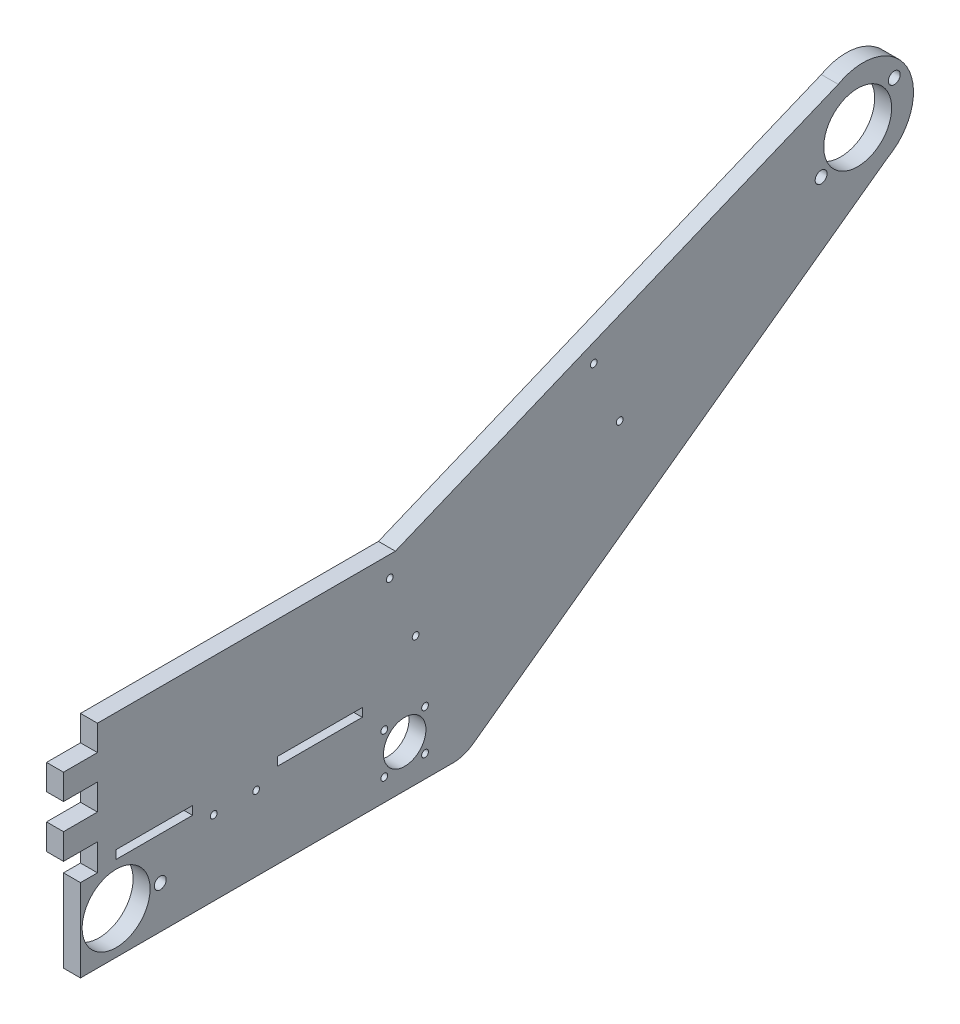
SolidWorks part; units mm, degrees
ref_plane "정면" through (0, 0, 0) normal (0, 0, 1) x (1, 0, 0)
ref_plane "윗면" through (0, 0, 0) normal (0, 1, 0) x (1, 0, 0)
ref_plane "우측면" through (0, 0, 0) normal (1, 0, 0) x (0, 0, -1)
sketch "스케치1" plane through (0, 0, 0) normal (1, 0, 0) x (0, 0, -1)
  line L0 (-325, 0) -> (325, 0) construction
  line L1 (325, 0) -> (591.861, 180) construction
  line L6 (-339, -14) -> (-311, -14) construction
  line L15 (-339, 14) -> (-311, 14) construction
  line L16 (-339, 14) -> (-339, -14) construction
  line L18 (-311, 14) -> (-311, -14) construction
  line L19 (-350, -25) -> (353.4809, -25)
  line L20 (311, 14) -> (311, -14) construction
  line L21 (339, 14) -> (339, -14) construction
  line L22 (339, 14) -> (311, 14) construction
  line L23 (339, -14) -> (311, -14) construction
  line L24 (-350, -25) -> (-350, 30)
  line L25 (300, 25) -> (350, 25) construction
  line L26 (-300, 25) -> (-350, 25) construction
  line L27 (-300, 25) -> (-300, -25) construction
  line L28 (300, 25) -> (300, -25) construction
  line L31 (365.2669, -21.1583) -> (609.4584, 155.7033)
  line L32 (580.4109, 207.729) -> (150, 30)
  line L34 (350, 25) -> (350, -25) construction
  line L35 (46, 52.6531) -> (46, -51.2062) construction
  line L36 (150, 37.2232) -> (150, -42.9076) construction
  line L39 (-350, 30) -> (150, 30)
  circle A0 centre (-325, 0) radius 12.5 construction
  circle A2 centre (-337, -12) radius 2 construction
  circle A3 centre (-313, -12) radius 2 construction
  circle A4 centre (-313, 12) radius 2 construction
  circle A5 centre (-337, 12) radius 2 construction
  circle A6 centre (337, 12) radius 2 construction
  circle A7 centre (313, 12) radius 2 construction
  circle A8 centre (313, -12) radius 2 construction
  circle A9 centre (337, -12) radius 2 construction
  circle A10 centre (325, 0) radius 12.5 construction
  circle A11 centre (0, 0) radius 7.5 construction
  circle A12 centre (0, 0) radius 20 construction
  circle A13 centre (-26, 0) radius 3.5 construction
  circle A14 centre (26, 0) radius 3.5 construction
  circle A15 centre (591.861, 180) radius 7.5 construction
  circle A16 centre (570.306, 165.461) radius 3.5 construction
  circle A17 centre (613.416, 194.539) radius 3.5 construction
  circle A18 centre (591.861, 180) radius 20 construction
  arc A24 (365.2669, -21.1583) -> (353.4809, -25) centre (353.4809, -5) cw
  arc A26 (580.4109, 207.729) -> (609.4584, 155.7033) centre (594.9347, 181.7161) cw
  point P3 (0, 0)
  dimension "D6" = 20
  dimension "D5" = 50
  dimension "D1" = 55
  dimension "D2" = 146
  dimension "D3" = 650
  dimension "D4" = 180
  dimension "D7" = 26
  dimension "D8" = 944.9347
extrude "보스-돌출2" add sketch "스케치1" along normal blind 10
sketch "스케치3" plane through (10, 0, 0) normal (1, 0, 0) x (0, 0, -1)
  circle A0 centre (613.416, 194.539) radius 3.5 construction
  circle A1 centre (570.306, 165.461) radius 3.5 construction
  circle A2 centre (591.861, 180) radius 20 construction
  circle A3 centre (337, -12) radius 2 construction
  circle A4 centre (313, 12) radius 2 construction
  circle A5 centre (313, -12) radius 2 construction
  circle A6 centre (337, 12) radius 2 construction
  circle A7 centre (325, 0) radius 12.5 construction
  circle A8 centre (26, 0) radius 3.5 construction
  circle A9 centre (-26, 0) radius 3.5 construction
  circle A10 centre (0, 0) radius 20 construction
  circle A11 centre (-313, -12) radius 2 construction
  circle A12 centre (-313, 12) radius 2 construction
  circle A13 centre (-325, 0) radius 12.5 construction
  circle A14 centre (-337, -12) radius 2 construction
  circle A15 centre (-337, 12) radius 2 construction
  circle A16 centre (613.416, 194.539) radius 3.5
  circle A17 centre (570.306, 165.461) radius 3.5
  circle A18 centre (591.861, 180) radius 20
  circle A19 centre (337, -12) radius 2
  circle A20 centre (313, 12) radius 2
  circle A21 centre (313, -12) radius 2
  circle A22 centre (337, 12) radius 2
  circle A23 centre (325, 0) radius 12.5
  circle A24 centre (26, 0) radius 3.5
  circle A25 centre (-26, 0) radius 3.5
  circle A26 centre (0, 0) radius 20
  circle A27 centre (-313, -12) radius 2
  circle A28 centre (-313, 12) radius 2
  circle A29 centre (-325, 0) radius 12.5
  circle A30 centre (-337, -12) radius 2
  circle A31 centre (-337, 12) radius 2
extrude "컷-돌출1" cut sketch "스케치3" against normal through all contours A29 | A27 | A30 | A31 | A28 | A23 | A20 | A21 | A19 | A22 | A18 | A16 | A17
sketch "스케치4" plane through (10, 0, 0) normal (1, 0, 0) x (0, 0, -1)
  line L2 (100, 25) -> (100, 30)
  line L4 (-50, 25) -> (-100, 25)
  line L6 (100, 25) -> (50, 25)
  line L7 (50, 25) -> (50, 30)
  line L8 (300, 25) -> (300, 30)
  line L9 (300, 30) -> (250, 30)
  line L10 (250, 30) -> (250, 25)
  line L11 (250, 25) -> (300, 25)
  line L13 (150, 30) -> (200, 30)
  line L14 (200, 30) -> (200, 25)
  line L15 (200, 25) -> (150, 25)
  line L16 (150, 25) -> (150, 30)
  line L17 (-100, 25) -> (-100, 30)
  line L19 (-50, 25) -> (-50, 30)
  line L21 (-300, 30) -> (-300, 35)
  line L24 (-300, 25) -> (-300, 30)
  line L25 (-300, 25) -> (-250, 25)
  line L26 (-250, 25) -> (-250, 30)
  line L28 (-200, 25) -> (-200, 30)
  line L29 (-200, 25) -> (-150, 25)
  line L30 (-150, 25) -> (-150, 30)
  line L32 (-250, 30) -> (-250, 35)
  line L33 (-150, 30) -> (-150, 35)
  line L34 (-200, 30) -> (-200, 35)
  line L35 (-100, 30) -> (-100, 35)
  line L36 (-50, 30) -> (-50, 35)
  line L37 (100, 30) -> (100, 35)
  line L38 (50, 30) -> (50, 35)
  line L40 (100, 35) -> (50, 35)
  line L41 (-150, 35) -> (-200, 35)
  line L42 (-100, 35) -> (-50, 35)
  line L43 (-250, 35) -> (-300, 35)
  circle A8 centre (-237.5, 19) radius 2
  circle A9 centre (-212.5, 19) radius 2
  circle A10 centre (-139.9962, 19) radius 2
  circle A11 centre (-114.9962, 19) radius 2
  circle A12 centre (112.5, 19) radius 2
  circle A13 centre (137.5, 19) radius 2
  circle A14 centre (212.5, 19) radius 2
  circle A15 centre (237.5, 19) radius 2
sketch "스케치6" plane through (0, 30, 0) normal (0, 1, 0) x (1, 0, 0)
  line L0 (10, -50) -> (10, -100)
  line L1 (0, 150) -> (0, -350) construction
  line L2 (10, -300) -> (10, -250)
  line L3 (0, 100) -> (0, 50)
  line L4 (10, -250) -> (10, -300) construction
  line L5 (10, -300) -> (10, -250) construction
  line L6 (10, -250) -> (0, -250)
  line L7 (10, -300) -> (0, -300)
  line L8 (10, -200) -> (10, -150)
  line L9 (10, -150) -> (10, -200) construction
  line L10 (10, -200) -> (10, -150) construction
  line L11 (10, -150) -> (0, -150)
  line L12 (10, -200) -> (0, -200)
  line L13 (10, -100) -> (0, -100)
  line L14 (10, -100) -> (10, -50) construction
  line L15 (10, -50) -> (10, -100) construction
  line L16 (10, -50) -> (0, -50)
  line L17 (0, -250) -> (0, -300)
  line L18 (10, 100) -> (10, 50)
  line L19 (10, 100) -> (10, 50) construction
  line L20 (10, 100) -> (10, 50) construction
  line L21 (10, 50) -> (0, 50)
  line L22 (10, 100) -> (0, 100)
  line L23 (0, -150) -> (0, -200)
  line L24 (0, -50) -> (0, -100)
extrude "컷-돌출14" cut sketch "스케치6" against normal blind 5
sketch "스케치7" plane through (10, 0, 0) normal (1, 0, 0) x (0, 0, -1)
  line L0 (155, 30) -> (200, 30)
  line L1 (200, 30) -> (200, 25)
  line L4 (250, 30) -> (250, 25)
  line L5 (250, 25) -> (300, 25)
  line L6 (300, 25) -> (300, 30)
  line L7 (300, 30) -> (250, 30)
  line L8 (155, 25) -> (200, 25)
  line L9 (200, 25) -> (150, 25) construction
  line L10 (155, 25) -> (155, 30)
extrude "컷-돌출17" cut sketch "스케치7" against normal through all
extrude "컷-돌출18" cut sketch "스케치4" against normal blind 10 contours A8 | A9 | A10 | A11 | A12 | A14 | A15
sketch "스케치8" plane through (0, 0, 350) normal (0, 0, 1) x (1, 0, 0)
  line L4 (0, 30) -> (0, -25)
  line L5 (0, -25) -> (10, -25)
  line L6 (10, -25) -> (10, 30)
  line L7 (10, 30) -> (0, 30)
  line L8 (0, 30) -> (0, -25)
  line L9 (0, -25) -> (10, -25)
  line L10 (10, -25) -> (10, 30)
  line L11 (10, 30) -> (0, 30)
  dimension "D1" = 0
extrude "보스-돌출3" add sketch "스케치8" along normal blind 10
sketch "스케치9" plane through (10, 0, 0) normal (1, 0, 0) x (0, 0, -1)
  circle A2 centre (-92.5, 0) radius 3.5
  circle A3 centre (-40.5, 0) radius 3.5
  circle A4 centre (-66.5, 0) radius 20
  circle A9 centre (155, 0) radius 20
  circle A10 centre (181, 0) radius 3.5
  circle A11 centre (129, 0) radius 3.5
extrude "컷-돌출19" cut sketch "스케치9" against normal through all
sketch "스케치10" plane through (0, 0, 0) normal (1, 0, 0) x (0, 0, -1)
  line L11 (100, 30) -> (100, 25)
  line L12 (100, 25) -> (50, 25)
  line L17 (50, 25) -> (50, 30)
  line L19 (-50, 100) -> (319.5208, 100)
  line L20 (580.4109, 207.729) -> (150, 30) construction
  line L21 (319.5208, 100) -> (150, 30)
  line L22 (150, 30) -> (100, 30)
  line L23 (50, 30) -> (-50, 30)
  line L24 (-50, 30) -> (-360, 30)
  line L25 (-360, 30) -> (-360, 100)
  line L26 (-360, 100) -> (-50, 100)
  point P12 (139.7616, 36.9837)
  point P13 (576.6226, 216.9837)
  dimension "D1" = 70
extrude "보스-돌출4" add sketch "스케치10" along normal blind 10
sketch "스케치14" plane through (10, 0, 0) normal (1, 0, 0) x (0, 0, -1)
  circle A3 centre (44.25, 11) radius 10 construction
  circle A4 centre (44.25, 11) radius 20
  circle A5 centre (70.25, 11) radius 3
  circle A7 centre (18.25, 11) radius 3
  point P0 (0, 0)
  dimension "D1" = 40
  dimension "D2" = 6
  dimension "D3" = 26
  dimension "D4" = 26
extrude "컷-돌출20" cut sketch "스케치14" against normal through all
sketch "스케치15" plane through (10, 0, 0) normal (1, 0, 0) x (0, 0, -1)
  line L0 (133.0091, 35.5821) -> (133.0091, 30.5821)
  line L7 (580.4109, 207.729) -> (319.5208, 100) construction
  circle A4 centre (331.4334, 50.824) radius 2
  circle A5 centre (316.195, 87.8077) radius 2
  circle A6 centre (451.6303, 100.3488) radius 2
  circle A7 centre (436.3919, 137.3324) radius 2
  point P1 (0, 0)
  point P3 (0, 0)
  point P24 (0, 0)
  point P26 (0, 0)
  dimension "D2" = 4
  dimension "D7" = 10
  dimension "D3" = 4
  dimension "D4" = 4
  dimension "D5" = 4
  dimension "D11" = 40
extrude "컷-돌출22" cut sketch "스케치15" against normal through all contours A5 | A4 | A7 | A6
sketch "스케치16" plane through (10, 0, 0) normal (1, 0, 0) x (0, 0, -1)
  line L0 (-11.5, 71.5023) -> (-11.5, -50.9694) construction
  line L1 (92.5, 71.5023) -> (92.5, -48.7682) construction
  circle A1 centre (-40.5, 0) radius 3.5 construction
  circle A5 centre (112.5, 19) radius 2 construction
  point P8 (92.5, 11.3671)
  dimension "D1" = 29
  dimension "D2" = 20
sketch "스케치17" plane through (10, 0, 0) normal (1, 0, 0) x (0, 0, -1)
  line L0 (319.5208, 100) -> (319.5208, -43.2034) construction
  line L4 (134, 100) -> (144, 100)
  line L6 (134, 114.9691) -> (134, -37.6192) construction
  line L7 (319.5208, 100) -> (-360, 100) construction
  line L17 (144, 114.9691) -> (144, -9.8458) construction
  line L19 (124, 114.9691) -> (124, -12.9668) construction
  line L20 (144, 100) -> (144, 85)
  line L21 (144, 85) -> (124, 85)
  line L22 (124, 85) -> (124, 70.0094)
  line L23 (124, 70.0094) -> (144, 70.0094)
  line L24 (144, 70.0094) -> (144, 54.646)
  line L25 (144, 54.646) -> (124, 54.646)
  line L26 (124, 54.646) -> (124, 39.4856)
  line L27 (124, 39.4856) -> (144, 39.4856)
  line L28 (144, 39.4856) -> (144, 23.6607)
  line L29 (144, 23.6607) -> (134, 23.6607)
  line L30 (134, 23.6607) -> (134, -25.2592)
  line L34 (134, 260.6848) -> (134, 100)
  line L35 (134, 260.6848) -> (-374.7269, 260.6848)
  line L36 (-374.7269, 260.6848) -> (-374.7269, -25.2592)
  line L37 (-374.7269, -25.2592) -> (134, -25.2592)
  dimension "D2" = 10
  dimension "D1" = 10
  dimension "D3" = 15
extrude "컷-돌출26" cut sketch "스케치17" against normal through all
